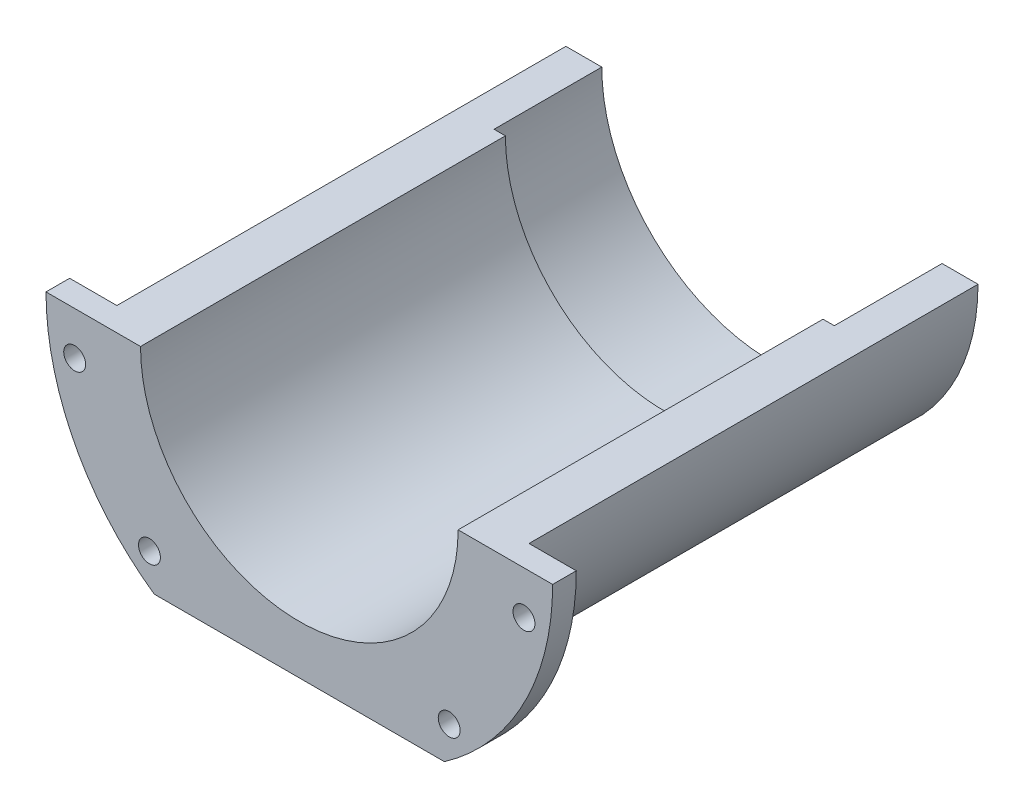
SolidWorks part; units mm, degrees
ref_plane "Front Plane" through (0, 0, 0) normal (0, 0, 1) x (1, 0, 0)
ref_plane "Top Plane" through (0, 0, 0) normal (0, 1, 0) x (1, 0, 0)
ref_plane "Right Plane" through (0, 0, 0) normal (1, 0, 0) x (0, 0, -1)
sketch "Sketch1" plane through (0, 0, 0) normal (0, 0, 1) x (1, 0, 0)
  circle A0 centre (0, 0) radius 21.336
  circle A1 centre (0, 0) radius 27.686
  circle A2 centre (0, 0) radius 40.386
extrude "Boss-Extrude1" add sketch "Sketch1" along normal blind 63.5 contours A1 A0
sketch "Sketch2" plane through (0, 0, 63.5) normal (0, 0, 1) x (1, 0, 0)
  circle A0 centre (0, 0) radius 34.036
  circle A1 centre (0, 0) radius 27.686
  circle A2 centre (0, 0) radius 21.336 construction
extrude "Boss-Extrude2" add sketch "Sketch2" against normal blind 3.175
sketch "Sketch3" plane through (0, 0, 60.325) normal (0, 0, -1) x (-1, 0, 0)
  line L1 (-45.3508, 0) -> (52.3653, 0)
  line L2 (-45.3508, 0) -> (-45.3508, 43.5972)
  line L3 (-45.3508, 43.5972) -> (52.3653, 43.5972)
  line L4 (52.3653, 0) -> (52.3653, 43.5972)
extrude "Cut-Extrude1" cut sketch "Sketch3" along normal blind 101.6 and the other way blind 101.6
sketch "Sketch4" plane through (0, 0, 60.325) normal (0, 0, -1) x (-1, 0, 0)
  circle A0 centre (0, 0) radius 30.7342
  circle A1 centre (-30.1839, -5.7898) radius 1.4732
  circle A2 centre (30.1839, -5.7898) radius 1.4732
  circle A3 centre (-20.1372, -23.2182) radius 1.4732
  circle A4 centre (20.1372, -23.2182) radius 1.4732
  circle A5 centre (0, -30.7342) radius 1.4732
  point P7 (0, 0)
  point P10 (0, 0)
  point P13 (0, 0)
  point P16 (0, 0)
  point P17 (0, 0)
  dimension "D1" = 20.1168
  dimension "D3" = 61.4684
  dimension "D5" = 2.9464
  dimension "D4" = 21.4941
extrude "Cut-Extrude2" cut sketch "Sketch4" against normal blind 101.6 contours A0 A1 | A0 A1 | A0 A3 | A0 A3 | A0 A4 | A0 A4 | A0 A2 | A0 A2 | A0 A5 | A0 A5
sketch "Sketch5" plane through (0, 0, 60.325) normal (0, 0, -1) x (-1, 0, 0)
  line L1 (-22.9355, -27.8989) -> (22.5548, -27.8989)
  line L2 (-22.9355, -27.8989) -> (-22.9355, -36.2736)
  line L3 (-22.9355, -36.2736) -> (22.5548, -36.2736)
  line L4 (22.5548, -27.8989) -> (22.5548, -36.2736)
extrude "Cut-Extrude3" cut sketch "Sketch5" against normal blind 101.6
ref_plane "Plane1" through (0, 0, 0) normal (0, 0, -1) x (-1, 0, 0)
sketch "Sketch6" plane through (0, 0, 0) normal (0, 0, -1) x (-1, 0, 0)
  circle A0 centre (0, 0) radius 22.86
extrude "Cut-Extrude4" cut sketch "Sketch6" against normal blind 14.478
